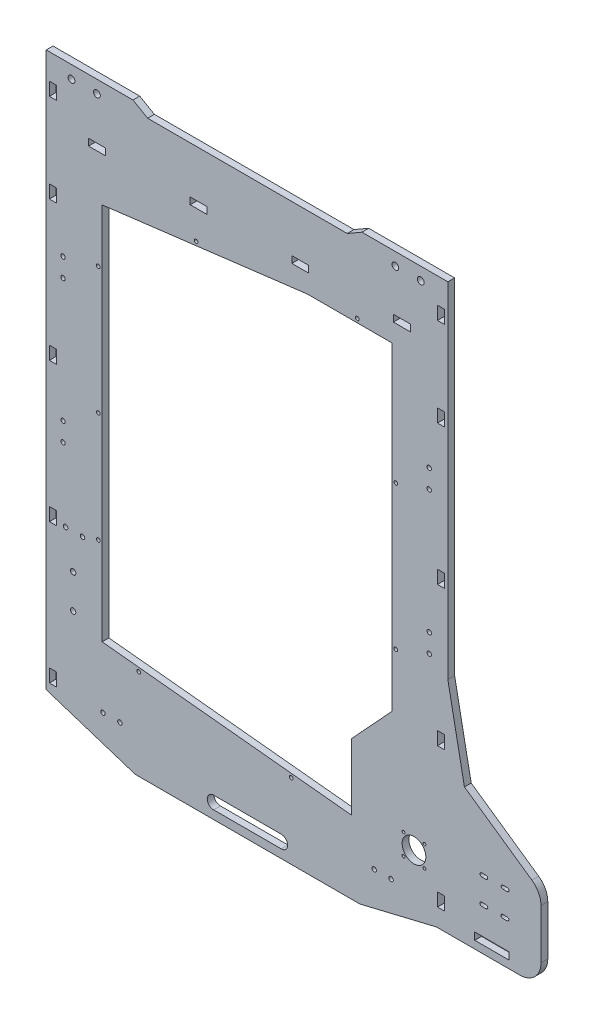
SolidWorks part; units mm, degrees
material "PMMA"
ref_plane "Plan de face" through (0, 0, 0) normal (0, 0, 1) x (1, 0, 0)
ref_plane "Plan de dessus" through (0, 0, 0) normal (0, 1, 0) x (1, 0, 0)
ref_plane "Plan de droite" through (0, 0, 0) normal (1, 0, 0) x (0, 0, -1)
sketch "Esquisse1" plane through (0, 0, 0) normal (0, 0, 1) x (1, 0, 0)
  line L0 (15.3297, -21) -> (-15.3297, -21) construction
  line L1 (40, -47) -> (-434.3, -47)
  line L2 (40, -47) -> (40, 601.3433)
  line L3 (40, 601.3433) -> (-61.5, 601.3433)
  line L4 (-434.3, -47) -> (-434.3, 601.3433)
  line L5 (14.85, 546) -> (9.1797, 546) construction
  line L6 (28, 17.5) -> (28, 23.1703) construction
  line L8 (-422.3, 50.99) -> (-422.3, 26.01) construction
  line L9 (-61.5, 601.3433) -> (-78.8205, 591.3433)
  line L10 (-78.8205, 591.3433) -> (-314.5264, 591.3433)
  line L11 (-196.6734, 568.0472) -> (-196.6734, 478.6085) construction
  line L12 (-331.8469, 601.3433) -> (-314.5264, 591.3433)
  line L13 (-331.8469, 601.3433) -> (-434.3, 601.3433)
  line L15 (-368.3, 505.8433) -> (-26, 505.8433)
  line L16 (-368.3, 505.8433) -> (-368.3, -1)
  line L17 (-368.3, -1) -> (-26, -1)
  line L18 (-26, 505.8433) -> (-26, -1)
  circle A0 centre (-12.3744, 12.3744) radius 1.7 construction
  circle A1 centre (12.3744, 12.3744) radius 1.7 construction
  circle A2 centre (-12.3744, -12.3744) radius 1.7 construction
  circle A3 centre (12.3744, -12.3744) radius 1.7 construction
  circle A4 centre (-12.3744, 12.3744) radius 1.7
  circle A5 centre (12.3744, 12.3744) radius 1.7
  circle A6 centre (-12.3744, -12.3744) radius 1.7
  circle A7 centre (12.3744, -12.3744) radius 1.7
  circle A8 centre (0, 0) radius 14 construction
  circle A9 centre (0, 0) radius 14
  point P19 (-196.6734, 591.3433)
  dimension "D2" = 12
  dimension "D3" = 95.5
  dimension "D4" = 12
  dimension "D5" = 30
  dimension "D6" = 101.5
  dimension "D7" = 117.8529
  dimension "D8" = 20
  dimension "D9" = 66
  dimension "D10" = 66
  dimension "D11" = 20
  dimension "D12" = 55.3433
  dimension "D13" = 46
extrude "Boss.-Extru.1" add sketch "Esquisse1" along normal blind 8
sketch "Esquisse2" plane through (0, 0, 8) normal (0, 0, 1) x (1, 0, 0)
  line L0 (40, 528) -> (-434.3, 528) construction
  line L1 (-434.3, 601.3433) -> (-434.3, -47) construction
  line L3 (40, -47) -> (40, 601.3433) construction
  line L4 (-434.3, 536) -> (40, 536) construction
  line L5 (-264.3, 528) -> (-244.3, 528)
  line L6 (-384.3, 528) -> (-364.3, 528)
  line L7 (-384.3, 528) -> (-384.3, 536)
  line L8 (-384.3, 536) -> (-364.3, 536)
  line L9 (-364.3, 528) -> (-364.3, 536)
  line L10 (-264.3, 528) -> (-264.3, 536)
  line L11 (-264.3, 536) -> (-244.3, 536)
  line L12 (-244.3, 528) -> (-244.3, 536)
  line L13 (-144.3, 528) -> (-124.3, 528)
  line L14 (-144.3, 528) -> (-144.3, 536)
  line L15 (-144.3, 536) -> (-124.3, 536)
  line L16 (-124.3, 528) -> (-124.3, 536)
  line L17 (-24.3, 528) -> (-4.3, 528)
  line L18 (-24.3, 528) -> (-24.3, 536)
  line L19 (-24.3, 536) -> (-4.3, 536)
  line L20 (-4.3, 528) -> (-4.3, 536)
  line L21 (-26, 505.8433) -> (-368.3, 505.8433) construction
  point P28 (-264.3, 532)
  dimension "D2" = 20
  dimension "D3" = 50
  dimension "D5" = 8
  dimension "D1" = 22.1567
  dimension "D6" = 100
  dimension "D4" = 4
extrude "Enlèv. mat.-Extru.1" cut sketch "Esquisse2" against normal blind 10
sketch "Esquisse4" plane through (0, 0, 8) normal (0, 0, 1) x (1, 0, 0)
  line L0 (36, -29) -> (28, -29) construction
  line L1 (28, -44) -> (36, -44) construction
  line L2 (28, -44) -> (28, -29) construction
  line L3 (28, -29) -> (36, -29) construction
  line L4 (36, -44) -> (36, -29) construction
  line L5 (36, -44) -> (36, -29) construction
  line L6 (27.75, -44.25) -> (36.25, -44.25)
  line L7 (36.25, -44.25) -> (36.25, -28.75)
  line L8 (27.75, -28.75) -> (36.25, -28.75)
  line L9 (27.75, -44.25) -> (27.75, -28.75)
  line L10 (36.25, 136.25) -> (27.75, 136.25)
  line L11 (36, 136) -> (28, 136) construction
  line L12 (36, 136) -> (36, 121) construction
  line L13 (36, 121) -> (28, 121) construction
  line L14 (28, 136) -> (28, 121) construction
  line L15 (27.75, 136.25) -> (27.75, 120.75)
  line L16 (36.25, 120.75) -> (27.75, 120.75)
  line L17 (36.25, 136.25) -> (36.25, 120.75)
  line L18 (27.75, 301.25) -> (36.25, 301.25)
  line L19 (28, 301) -> (36, 301) construction
  line L20 (28, 301) -> (28, 286) construction
  line L21 (28, 286) -> (36, 286) construction
  line L22 (36, 301) -> (36, 286) construction
  line L23 (36.25, 301.25) -> (36.25, 285.75)
  line L24 (27.75, 285.75) -> (36.25, 285.75)
  line L25 (27.75, 301.25) -> (27.75, 285.75)
  line L26 (27.75, 466.25) -> (36.25, 466.25)
  line L27 (28, 466) -> (36, 466) construction
  line L28 (28, 466) -> (28, 451) construction
  line L29 (28, 451) -> (36, 451) construction
  line L30 (36, 466) -> (36, 451) construction
  line L31 (36.25, 466.25) -> (36.25, 450.75)
  line L32 (27.75, 450.75) -> (36.25, 450.75)
  line L33 (27.75, 466.25) -> (27.75, 450.75)
  line L34 (36, 556) -> (28, 556) construction
  line L35 (28, 571) -> (36, 571) construction
  line L36 (28, 571) -> (28, 556) construction
  line L37 (28, 556) -> (36, 556) construction
  line L38 (36, 571) -> (36, 556) construction
  line L39 (36, 556) -> (36, 571) construction
  line L40 (27.75, 571.25) -> (36.25, 571.25)
  line L41 (36.25, 571.25) -> (36.25, 555.75)
  line L42 (27.75, 555.75) -> (36.25, 555.75)
  line L43 (27.75, 571.25) -> (27.75, 555.75)
  dimension "D1" = 0.25
  dimension "D2" = 0.25
  dimension "D3" = 0.25
  dimension "D4" = 0.25
  dimension "D5" = 0.25
extrude "Enlèv. mat.-Extru.2" cut sketch "Esquisse4" against normal blind 10
sketch "Esquisse5" plane through (0, 0, 8) normal (0, 0, 1) x (1, 0, 0)
  line L0 (27.75, 571.25) -> (27.75, 555.75) construction
  line L1 (27.75, 555.75) -> (36.25, 555.75) construction
  line L2 (36.25, 555.75) -> (36.25, 571.25) construction
  line L3 (36.25, 571.25) -> (27.75, 571.25) construction
  line L4 (27.75, 571.25) -> (27.75, 555.75) construction
  line L5 (27.75, 555.75) -> (36.25, 555.75) construction
  line L6 (36.25, 555.75) -> (36.25, 571.25) construction
  line L7 (36.25, 571.25) -> (27.75, 571.25) construction
  line L8 (27.75, -44.25) -> (36.25, -44.25) construction
  line L9 (36.25, -44.25) -> (36.25, -28.75) construction
  line L10 (27.75, -28.75) -> (27.75, -44.25) construction
  line L11 (36.25, -28.75) -> (27.75, -28.75) construction
  line L12 (27.75, 136.25) -> (27.75, 120.75) construction
  line L13 (27.75, 120.75) -> (36.25, 120.75) construction
  line L14 (36.25, 120.75) -> (36.25, 136.25) construction
  line L15 (36.25, 136.25) -> (27.75, 136.25) construction
  line L16 (27.75, 301.25) -> (27.75, 285.75) construction
  line L17 (36.25, 301.25) -> (27.75, 301.25) construction
  line L18 (36.25, 285.75) -> (36.25, 301.25) construction
  line L19 (27.75, 285.75) -> (36.25, 285.75) construction
  line L20 (36.25, 450.75) -> (36.25, 466.25) construction
  line L21 (27.75, 450.75) -> (36.25, 450.75) construction
  line L22 (27.75, 466.25) -> (27.75, 450.75) construction
  line L23 (36.25, 466.25) -> (27.75, 466.25) construction
  line L24 (27.75, -44.25) -> (36.25, -44.25) construction
  line L25 (36.25, -44.25) -> (36.25, -28.75) construction
  line L26 (27.75, -28.75) -> (27.75, -44.25) construction
  line L27 (36.25, -28.75) -> (27.75, -28.75) construction
  line L28 (27.75, 136.25) -> (27.75, 120.75) construction
  line L29 (27.75, 120.75) -> (36.25, 120.75) construction
  line L30 (36.25, 120.75) -> (36.25, 136.25) construction
  line L31 (36.25, 136.25) -> (27.75, 136.25) construction
  line L32 (27.75, 301.25) -> (27.75, 285.75) construction
  line L33 (36.25, 301.25) -> (27.75, 301.25) construction
  line L34 (36.25, 285.75) -> (36.25, 301.25) construction
  line L35 (27.75, 285.75) -> (36.25, 285.75) construction
  line L36 (36.25, 450.75) -> (36.25, 466.25) construction
  line L37 (27.75, 450.75) -> (36.25, 450.75) construction
  line L38 (27.75, 466.25) -> (27.75, 450.75) construction
  line L39 (36.25, 466.25) -> (27.75, 466.25) construction
  line L40 (-197.15, -47) -> (-197.15, 394.0734) construction
  line L43 (-434.3, -47) -> (40, -47) construction
  line L44 (-430.55, 466.25) -> (-422.05, 466.25)
  line L45 (-422.05, 466.25) -> (-422.05, 450.75)
  line L46 (-422.05, 450.75) -> (-430.55, 450.75)
  line L47 (-430.55, 450.75) -> (-430.55, 466.25)
  line L48 (-422.05, 285.75) -> (-430.55, 285.75)
  line L49 (-430.55, 285.75) -> (-430.55, 301.25)
  line L50 (-430.55, 301.25) -> (-422.05, 301.25)
  line L51 (-422.05, 301.25) -> (-422.05, 285.75)
  line L52 (-430.55, 136.25) -> (-422.05, 136.25)
  line L53 (-430.55, 120.75) -> (-430.55, 136.25)
  line L54 (-422.05, 120.75) -> (-430.55, 120.75)
  line L55 (-422.05, 136.25) -> (-422.05, 120.75)
  line L56 (-430.55, -28.75) -> (-422.05, -28.75)
  line L57 (-422.05, -28.75) -> (-422.05, -44.25)
  line L58 (-430.55, -44.25) -> (-430.55, -28.75)
  line L59 (-422.05, -44.25) -> (-430.55, -44.25)
  line L60 (-430.55, 571.25) -> (-422.05, 571.25)
  line L61 (-430.55, 555.75) -> (-430.55, 571.25)
  line L62 (-422.05, 555.75) -> (-430.55, 555.75)
  line L63 (-422.05, 571.25) -> (-422.05, 555.75)
extrude "Enlèv. mat.-Extru.3" cut sketch "Esquisse5" against normal blind 10
sketch "Esquisse6" plane through (0, 0, 8) normal (0, 0, 1) x (1, 0, 0)
  circle A0 centre (-402.5, 83.4) radius 3.15 construction
  circle A1 centre (-402.5, 43.4) radius 3.15 construction
  circle A2 centre (-402.5, 83.4) radius 3.15
  circle A3 centre (-402.5, 43.4) radius 3.15
  circle A4 centre (-391.4386, 124.84) radius 2.65 construction
  circle A5 centre (-411.4386, 124.84) radius 2.65 construction
  circle A6 centre (-391.4386, 124.84) radius 2.65
  circle A7 centre (-411.4386, 124.84) radius 2.65
extrude "Enlèv. mat.-Extru.4" cut sketch "Esquisse6" against normal blind 10
sketch "Esquisse8" plane through (0, 0, 8) normal (0, 0, 1) x (1, 0, 0)
  line L6 (-368.3, 505.8433) -> (-368.3, 475.8433)
  line L7 (-368.3, 505.8433) -> (-368.3, -1) construction
  line L8 (-368.3, 475.8433) -> (-126, 505.8433)
  line L9 (-26, 505.8433) -> (-368.3, 505.8433) construction
  line L10 (-126, 505.8433) -> (-368.3, 505.8433)
  line L11 (-26, -1) -> (-26, 505.8433) construction
  line L12 (-74, -1) -> (-74, 77)
  line L13 (-368.3, -1) -> (-26, -1) construction
  line L14 (-74, 77) -> (-26, 129)
  line L15 (-26, 129) -> (-26, -1)
  line L16 (-26, -1) -> (-74, -1)
  line L17 (-74, -1) -> (-368.3, 29)
  line L19 (-368.3, 29) -> (-368.3, -1)
  line L20 (-368.3, -1) -> (-74, -1)
  dimension "D1" = 100
  dimension "D2" = 30
  dimension "D3" = 48
  dimension "D4" = 30
  dimension "D5" = 78
  dimension "D6" = 130
extrude "Boss.-Extru.2" add sketch "Esquisse8" against normal blind 8 contours L16 L15 L14 L12 | L19 L20 L17 | L8 L10 L6
sketch "Esquisse9" plane through (0, 0, 8) normal (0, 0, 1) x (1, 0, 0)
  line L0 (-434.3, -47) -> (-434.3, -53)
  line L1 (-434.3, -53) -> (-329.3, -87)
  line L2 (-329.3, -87) -> (-64, -87)
  line L3 (-64, -87) -> (40, -62)
  line L4 (40, -62) -> (40, -47)
  line L5 (-434.3, -47) -> (40, -47) construction
  line L6 (-236.65, -69.5) -> (-156.65, -69.5) construction
  line L7 (-236.65, -62) -> (-156.65, -62)
  line L8 (-236.65, -77) -> (-156.65, -77)
  line L9 (-434.3, -47) -> (40, -47)
  arc A0 (-236.65, -62) -> (-236.65, -77) centre (-236.65, -69.5) ccw
  arc A1 (-156.65, -77) -> (-156.65, -62) centre (-156.65, -69.5) ccw
  point P12 (-196.65, -69.5)
  point P17 (-196.65, -87)
  point P18 (-196.65, -77)
  dimension "D1" = 6
  dimension "D2" = 15
  dimension "D3" = 40
  dimension "D4" = 104
  dimension "D5" = 105
  dimension "D6" = 15
  dimension "D7" = 10
  dimension "D8" = 80
extrude "Boss.-Extru.3" add sketch "Esquisse9" against normal blind 8
sketch "Esquisse11" plane through (0, 0, 0) normal (0, 0, -1) x (-1, 0, 0)
  line L0 (-40, -62) -> (-117, -43.4904)
  line L1 (64, -87) -> (-40, -62) construction
  line L2 (-117, -43.4904) -> (-117, 54.5096)
  line L3 (-117, 54.5096) -> (-59.5544, 94.5096)
  line L4 (-59.5544, 94.5096) -> (-40, 194.5096)
  line L5 (-40, -62) -> (-40, 601.3433) construction
  line L6 (-40, 194.5096) -> (-40, -62)
  dimension "D1" = 98
  dimension "D2" = 77
  dimension "D3" = 40
  dimension "D4" = 100
  dimension "D5" = 70
extrude "Boss.-Extru.4" add sketch "Esquisse11" against normal blind 8
sketch "Esquisse14" plane through (0, 0, 8) normal (0, 0, 1) x (1, 0, 0)
  line L0 (26.5, -65.2452) -> (117, -65.2452)
  line L1 (-64, -87) -> (117, -43.4904) construction
  line L2 (117, -65.2452) -> (117, -43.4904)
  line L3 (117, 54.5096) -> (117, -43.4904) construction
  line L4 (117, -43.4904) -> (26.5, -65.2452)
extrude "Boss.-Extru.5" add sketch "Esquisse14" against normal blind 8
sketch "Esquisse13" plane through (0, 0, 8) normal (0, 0, 1) x (1, 0, 0)
  line L0 (71.75, -56.25) -> (112.25, -56.25)
  line L1 (112.25, -56.25) -> (112.25, -47.75)
  line L2 (112.25, -47.75) -> (71.75, -47.75)
  line L3 (71.75, -47.75) -> (71.75, -56.25)
  line L4 (72, -56) -> (112, -56)
  line L5 (112, -56) -> (112, -48)
  line L6 (112, -48) -> (72, -48)
  line L7 (72, -48) -> (72, -56)
  line L8 (72, -56) -> (112, -56) construction
  line L9 (112, -56) -> (112, -48) construction
  line L10 (112, -48) -> (72, -48) construction
  line L11 (72, -48) -> (72, -56) construction
  dimension "D1" = 0
  dimension "D2" = 0.25
extrude "Enlèv. mat.-Extru.6" cut sketch "Esquisse13" against normal blind 10
sketch "Esquisse15" plane through (0, 0, 8) normal (0, 0, 1) x (1, 0, 0)
  line L0 (20.5, 402.5) -> (20.5, 397.5) construction
  line L1 (15.5, 397.5) -> (15.5, 402.5) construction
  line L2 (20.5, 380.5) -> (20.5, 375.5) construction
  line L3 (15.5, 375.5) -> (15.5, 380.5) construction
  line L4 (-411.9386, 402.5) -> (-411.9386, 397.5) construction
  line L5 (-416.9386, 397.5) -> (-416.9386, 402.5) construction
  line L6 (-411.9386, 380.5) -> (-411.9386, 375.5) construction
  line L7 (-416.9386, 375.5) -> (-416.9386, 380.5) construction
  line L8 (20.5, 402.5) -> (20.5, 397.5) construction
  line L9 (15.5, 397.5) -> (15.5, 402.5) construction
  line L10 (20.5, 380.5) -> (20.5, 375.5) construction
  line L11 (15.5, 375.5) -> (15.5, 380.5) construction
  line L12 (-411.9386, 402.5) -> (-411.9386, 397.5) construction
  line L13 (-416.9386, 397.5) -> (-416.9386, 402.5) construction
  line L14 (-411.9386, 380.5) -> (-411.9386, 375.5) construction
  line L15 (-416.9386, 375.5) -> (-416.9386, 380.5) construction
  line L16 (18, 375.5) -> (18, 380.5) construction
  line L17 (18, 397.5) -> (18, 402.5) construction
  line L18 (-414.4386, 375.5) -> (-414.4386, 380.5) construction
  line L19 (-414.4386, 397.5) -> (-414.4386, 402.5) construction
  arc A0 (20.5, 402.5) -> (15.5, 402.5) centre (18, 402.5) ccw construction
  arc A1 (15.5, 397.5) -> (20.5, 397.5) centre (18, 397.5) ccw construction
  arc A2 (20.5, 380.5) -> (15.5, 380.5) centre (18, 380.5) ccw construction
  arc A3 (15.5, 375.5) -> (20.5, 375.5) centre (18, 375.5) ccw construction
  arc A4 (-411.9386, 402.5) -> (-416.9386, 402.5) centre (-414.4386, 402.5) ccw construction
  arc A5 (-416.9386, 397.5) -> (-411.9386, 397.5) centre (-414.4386, 397.5) ccw construction
  arc A6 (-411.9386, 380.5) -> (-416.9386, 380.5) centre (-414.4386, 380.5) ccw construction
  arc A7 (-416.9386, 375.5) -> (-411.9386, 375.5) centre (-414.4386, 375.5) ccw construction
  arc A8 (20.5, 402.5) -> (15.5, 402.5) centre (18, 402.5) ccw construction
  arc A9 (15.5, 397.5) -> (20.5, 397.5) centre (18, 397.5) ccw construction
  arc A10 (20.5, 380.5) -> (15.5, 380.5) centre (18, 380.5) ccw construction
  arc A11 (15.5, 375.5) -> (20.5, 375.5) centre (18, 375.5) ccw construction
  arc A12 (-411.9386, 402.5) -> (-416.9386, 402.5) centre (-414.4386, 402.5) ccw construction
  arc A13 (-416.9386, 397.5) -> (-411.9386, 397.5) centre (-414.4386, 397.5) ccw construction
  arc A14 (-411.9386, 380.5) -> (-416.9386, 380.5) centre (-414.4386, 380.5) ccw construction
  arc A15 (-416.9386, 375.5) -> (-411.9386, 375.5) centre (-414.4386, 375.5) ccw construction
  circle A16 centre (-414.4386, 378) radius 2.6
  circle A17 centre (-414.4386, 400) radius 2.6
  circle A18 centre (18, 400) radius 2.6
  circle A19 centre (18, 378) radius 2.6
  dimension "D1" = 5.2
  dimension "D2" = 5.2
  dimension "D3" = 5.2
  dimension "D4" = 5.2
extrude "Enlèv. mat.-Extru.7" cut sketch "Esquisse15" against normal blind 10
sketch "Esquisse16" plane through (0, 0, 8) normal (0, 0, 1) x (1, 0, 0)
  line L0 (117, 54.5096) -> (150, 31.5314)
  line L1 (59.5544, 94.5096) -> (117, 54.5096) construction
  line L2 (117, -65.2452) -> (150, -65.2452)
  line L3 (150, -65.2452) -> (150, 31.5314)
  line L4 (117, -65.2452) -> (117, 54.5096)
  dimension "D1" = 33
extrude "Boss.-Extru.6" add sketch "Esquisse16" against normal blind 8
fillet "Congé1" radius 25 2 edges at (150, 31.5314, 4) (150, -65.2452, 4)
sketch "Esquisse17" plane through (0, 0, 8) normal (0, 0, 1) x (1, 0, 0)
  circle A0 centre (-404.4386, 586.3433) radius 4 construction
  circle A1 centre (-374.4386, 586.3433) radius 4 construction
  circle A2 centre (-22, 586.3433) radius 4 construction
  circle A3 centre (8, 586.3433) radius 4 construction
  circle A4 centre (-404.4386, 586.3433) radius 4
  circle A5 centre (-374.4386, 586.3433) radius 4
  circle A6 centre (-22, 586.3433) radius 4
  circle A7 centre (8, 586.3433) radius 4
extrude "Enlèv. mat.-Extru.8" cut sketch "Esquisse17" against normal blind 10
sketch "Esquisse19" plane through (0, 0, 8) normal (0, 0, 1) x (1, 0, 0)
  line L0 (110, -15.2452) -> (105, -15.2452) construction
  line L1 (110, -17.3452) -> (105, -17.3452)
  line L2 (110, -13.1452) -> (105, -13.1452)
  line L3 (80, -15.2452) -> (85, -15.2452) construction
  line L4 (80, -13.1152) -> (85, -13.1152)
  line L5 (80, -17.3752) -> (85, -17.3752)
  line L6 (110, 14.7548) -> (105, 14.7548) construction
  line L7 (110, 12.6548) -> (105, 12.6548)
  line L8 (110, 16.8548) -> (105, 16.8548)
  line L9 (80, 14.7548) -> (85, 14.7548) construction
  line L10 (80, 16.8548) -> (85, 16.8548)
  line L11 (80, 12.6548) -> (85, 12.6548)
  arc A0 (110, -17.3452) -> (110, -13.1452) centre (110, -15.2452) ccw
  arc A1 (105, -13.1452) -> (105, -17.3452) centre (105, -15.2452) ccw
  arc A2 (80, -13.1152) -> (80, -17.3752) centre (80, -15.2452) ccw
  arc A3 (85, -17.3752) -> (85, -13.1152) centre (85, -15.2452) ccw
  arc A4 (110, 12.6548) -> (110, 16.8548) centre (110, 14.7548) ccw
  arc A5 (105, 16.8548) -> (105, 12.6548) centre (105, 14.7548) ccw
  arc A6 (80, 16.8548) -> (80, 12.6548) centre (80, 14.7548) ccw
  arc A7 (85, 12.6548) -> (85, 16.8548) centre (85, 14.7548) ccw
  point P3 (107.5, -15.2452)
  point P11 (82.5, -15.2452)
  point P19 (107.5, 14.7548)
  point P24 (82.5, 14.7548)
  dimension "D1" = 2.1
  dimension "D3" = 2.13
  dimension "D5" = 2.1
  dimension "D7" = 2.1
  dimension "D2" = 5
  dimension "D4" = 5
  dimension "D6" = 5
  dimension "D8" = 5
extrude "Enlèv. mat.-Extru.9" cut sketch "Esquisse19" against normal blind 10
sketch "Esquisse20" plane through (0, 0, 8) normal (0, 0, 1) x (1, 0, 0)
  circle A0 centre (-21.5, 194.8433) radius 2.15 construction
  circle A1 centre (-21.5, 364.8433) radius 2.15 construction
  circle A2 centre (-67, 510.3433) radius 2.15 construction
  circle A3 centre (-257.3, 494.1209) radius 2.15 construction
  circle A4 centre (-372.8, 410.8708) radius 2.15 construction
  circle A5 centre (-372.8, 260.8708) radius 2.15 construction
  circle A6 centre (-372.8, 130.8708) radius 2.15 construction
  circle A7 centre (-325, 20.0628) radius 2.15 construction
  circle A8 centre (-145, 1.7142) radius 2.15 construction
  circle A9 centre (-21.5, 194.8433) radius 2.15
  circle A10 centre (-21.5, 364.8433) radius 2.15
  circle A11 centre (-67, 510.3433) radius 2.15
  circle A12 centre (-257.3, 494.1209) radius 2.15
  circle A13 centre (-372.8, 410.8708) radius 2.15
  circle A14 centre (-372.8, 260.8708) radius 2.15
  circle A15 centre (-372.8, 130.8708) radius 2.15
  circle A16 centre (-325, 20.0628) radius 2.15
  circle A17 centre (-145, 1.7142) radius 2.15
extrude "Enlèv. mat.-Extru.10" cut sketch "Esquisse20" against normal blind 30
sketch "Esquisse21" plane through (0, 0, 0) normal (0, 0, -1) x (-1, 0, 0)
  circle A0 centre (47, -43) radius 2.6 construction
  circle A1 centre (27, -43) radius 2.6 construction
  circle A2 centre (367.3, -43) radius 2.6 construction
  circle A3 centre (347.3, -43) radius 2.6 construction
  circle A4 centre (47, -43) radius 2.6
  circle A5 centre (27, -43) radius 2.6
  circle A6 centre (367.3, -43) radius 2.6
  circle A7 centre (347.3, -43) radius 2.6
extrude "Enlèv. mat.-Extru.11" cut sketch "Esquisse21" against normal blind 11
sketch "Esquisse22" plane through (0, 0, 0) normal (0, 0, -1) x (-1, 0, 0)
  line L0 (-18, 378) -> (-18, 171.3734) construction
  line L1 (414.4386, 378) -> (414.4386, 171.3734) construction
  line L2 (434.3, 232) -> (-40, 232) construction
  line L3 (434.3, 601.3433) -> (434.3, -53) construction
  line L4 (-40, 194.5096) -> (-40, 601.3433) construction
  line L5 (434.3, 210) -> (-40, 210) construction
  line L6 (-27.75, 285.75) -> (-36.25, 285.75) construction
  circle A0 centre (-18, 232) radius 2.6
  circle A1 centre (-18, 210) radius 2.6
  circle A2 centre (414.4386, 232) radius 2.6
  circle A3 centre (414.4386, 210) radius 2.6
  dimension "D3" = 5.2
  dimension "D4" = 5.2
  dimension "D5" = 5.2
  dimension "D6" = 5.2
  dimension "D1" = 53.75
  dimension "D2" = 22
extrude "Enlèv. mat.-Extru.12" cut sketch "Esquisse22" against normal blind 10
